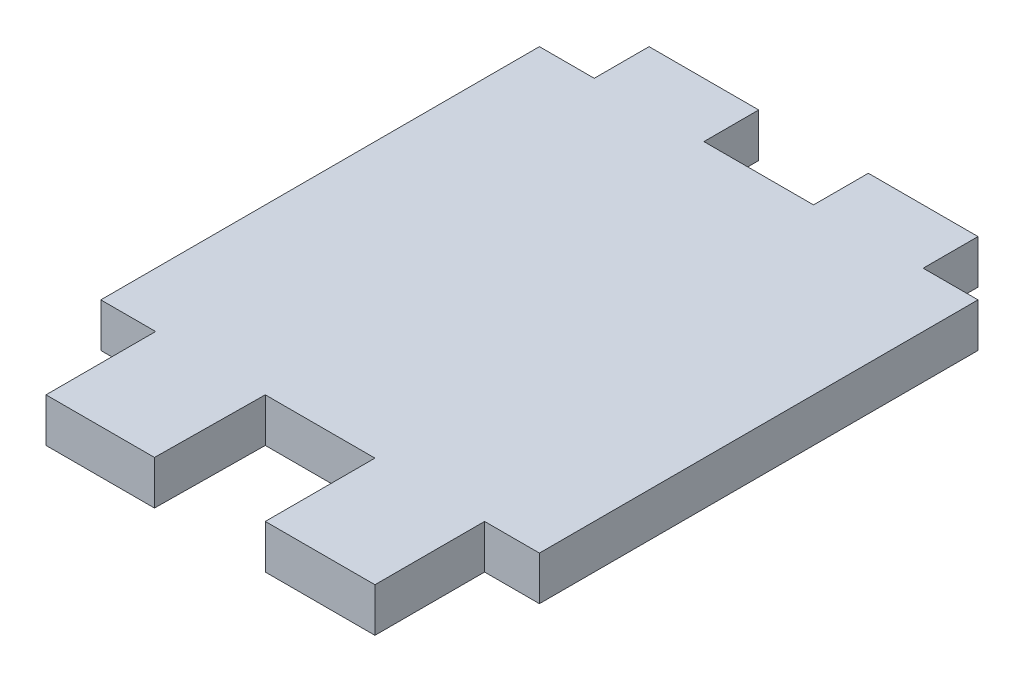
SolidWorks part; units mm, degrees
ref_plane "Front Plane" through (0, 0, 0) normal (0, 0, 1) x (1, 0, 0)
ref_plane "Top Plane" through (0, 0, 0) normal (0, 1, 0) x (1, 0, 0)
ref_plane "Right Plane" through (0, 0, 0) normal (1, 0, 0) x (0, 0, -1)
sketch "Sketch1" plane through (0, 0, 0) normal (0, 1, 0) x (1, 0, 0)
  line L0 (-29.4669, 30.541) -> (-34.4669, 30.541)
  line L1 (5.5331, 30.541) -> (5.5331, -9.459)
  line L2 (0.5331, 30.541) -> (0.5331, -19.459) construction
  line L3 (-34.4669, 30.541) -> (-34.4669, -9.459)
  line L4 (-9.4669, 30.541) -> (-9.4669, -19.459) construction
  line L5 (-19.4669, -19.459) -> (-29.4669, -19.459) construction
  line L6 (0.5331, 30.541) -> (0.5331, 35.541)
  line L7 (0.5331, 35.541) -> (-9.4669, 35.541)
  line L8 (-9.4669, 35.541) -> (-9.4669, 30.541)
  line L9 (-9.4669, 30.541) -> (-19.4669, 30.541)
  line L10 (-19.4669, 30.541) -> (-19.4669, 35.541)
  line L11 (-19.4669, 35.541) -> (-29.4669, 35.541)
  line L12 (-29.4669, 35.541) -> (-29.4669, 30.541)
  line L14 (-19.4669, -19.459) -> (-19.4669, 30.541) construction
  line L15 (0.5331, 30.541) -> (5.5331, 30.541)
  line L16 (-29.4669, 30.541) -> (-29.4669, -19.459) construction
  line L17 (0.5331, -19.459) -> (-9.4669, -19.459) construction
  line L18 (5.5331, -9.459) -> (0.5331, -9.459)
  line L19 (0.5331, -9.459) -> (0.5331, -19.459)
  line L20 (0.5331, -19.459) -> (-9.4669, -19.459)
  line L21 (-9.4669, -19.459) -> (-9.4669, -9.459)
  line L22 (-9.4669, -9.459) -> (-19.4669, -9.459)
  line L23 (-19.4669, -9.459) -> (-19.5743, -19.459)
  line L24 (-19.5743, -19.459) -> (-29.4669, -19.459)
  line L25 (-29.4669, -19.459) -> (-29.4669, -9.459)
  line L26 (-29.4669, -9.459) -> (-34.4669, -9.459)
  point P10 (-29.4669, 33.041)
  point P19 (-19.4669, 33.041)
  dimension "D1" = 10
  dimension "D5" = 5
  dimension "D6" = 10
  dimension "D7" = 10
extrude "Boss-Extrude1" add sketch "Sketch1" along normal blind 4
